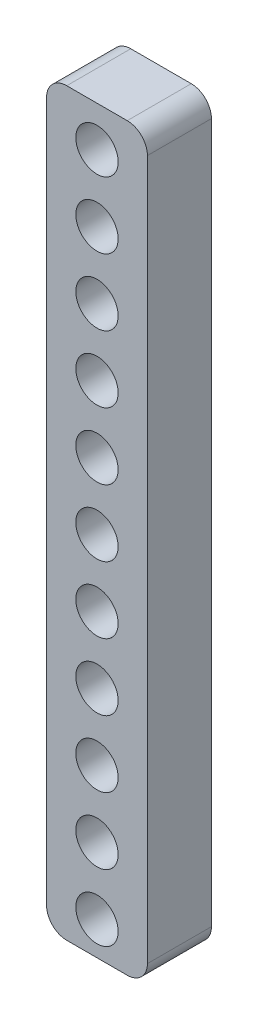
SolidWorks part; units mm, degrees
material "ABS"
ref_plane "Front Plane" through (0, 0, 0) normal (0, 0, 1) x (1, 0, 0)
ref_plane "Top Plane" through (0, 0, 0) normal (0, 1, 0) x (1, 0, 0)
ref_plane "Right Plane" through (0, 0, 0) normal (1, 0, 0) x (0, 0, -1)
sketch "Sketch1" plane through (0, 0, 0) normal (0, 0, 1) x (1, 0, 0)
  line L0 (0, -80) -> (0, 80) construction
  line L1 (3, -80) -> (-3, -80)
  line L2 (5, -78) -> (5, 78)
  line L3 (3, 80) -> (-3, 80)
  line L4 (-5, -78) -> (-5, 78)
  line L5 (5, -80) -> (-5, 80) construction
  line L6 (5, 80) -> (-5, -80) construction
  circle A1 centre (0, 76) radius 2.1
  circle A2 centre (0, 69.3913) radius 2.1
  circle A3 centre (0, 62.7826) radius 2.1
  circle A4 centre (0, 56.1739) radius 2.1
  circle A5 centre (0, 49.5652) radius 2.1
  circle A6 centre (0, 42.9565) radius 2.1
  circle A7 centre (0, 36.3478) radius 2.1
  circle A8 centre (0, 29.7391) radius 2.1
  circle A9 centre (0, 23.1304) radius 2.1
  circle A10 centre (0, 16.5217) radius 2.1
  circle A11 centre (0, 9.913) radius 2.1
  circle A12 centre (0, 3.3043) radius 2.1
  circle A13 centre (0, -3.3043) radius 2.1
  circle A14 centre (0, -9.913) radius 2.1
  circle A15 centre (0, -16.5217) radius 2.1
  circle A16 centre (0, -23.1304) radius 2.1
  circle A17 centre (0, -29.7391) radius 2.1
  circle A18 centre (0, -36.3478) radius 2.1
  circle A19 centre (0, -42.9565) radius 2.1
  circle A20 centre (0, -49.5652) radius 2.1
  circle A21 centre (0, -56.1739) radius 2.1
  circle A22 centre (0, -62.7826) radius 2.1
  circle A23 centre (0, -69.3913) radius 2.1
  circle A24 centre (0, -76) radius 2.1
  arc A25 (-3, -80) -> (-5, -78) centre (-3, -78) cw
  arc A26 (3, -80) -> (5, -78) centre (3, -78) ccw
  arc A27 (5, 78) -> (3, 80) centre (3, 78) ccw
  arc A28 (-3, 80) -> (-5, 78) centre (-3, 78) ccw
  point P0 (0, 0)
  dimension "D3" = 4.2
  dimension "D7" = 2
  dimension "D1" = 160
  dimension "D2" = 10
  dimension "D4" = 4
  dimension "D6" = 4
  dimension "D5" = 24
extrude "Boss-Extrude1" add sketch "Sketch1" along normal blind 6.35
sketch "Sketch2" plane through (0, 0, 0) normal (0, 0, -1) x (-1, 0, 0)
  line L0 (0, 9.913) -> (0, 6.6087) construction
  line L1 (8.8563, 6.6087) -> (-9.3483, 6.6087)
  line L2 (8.8563, 6.6087) -> (8.8563, -85.234)
  line L3 (8.8563, -85.234) -> (-9.3483, -85.234)
  line L4 (-9.3483, 6.6087) -> (-9.3483, -85.234)
  line L5 (0, 6.6087) -> (0, 3.3043) construction
extrude "Cut-Extrude1" cut sketch "Sketch2" against normal through all
fillet "Fillet2" radius 2 2 edges at (5, 6.6087, 3.175) (-5, 6.6087, 3.175)
